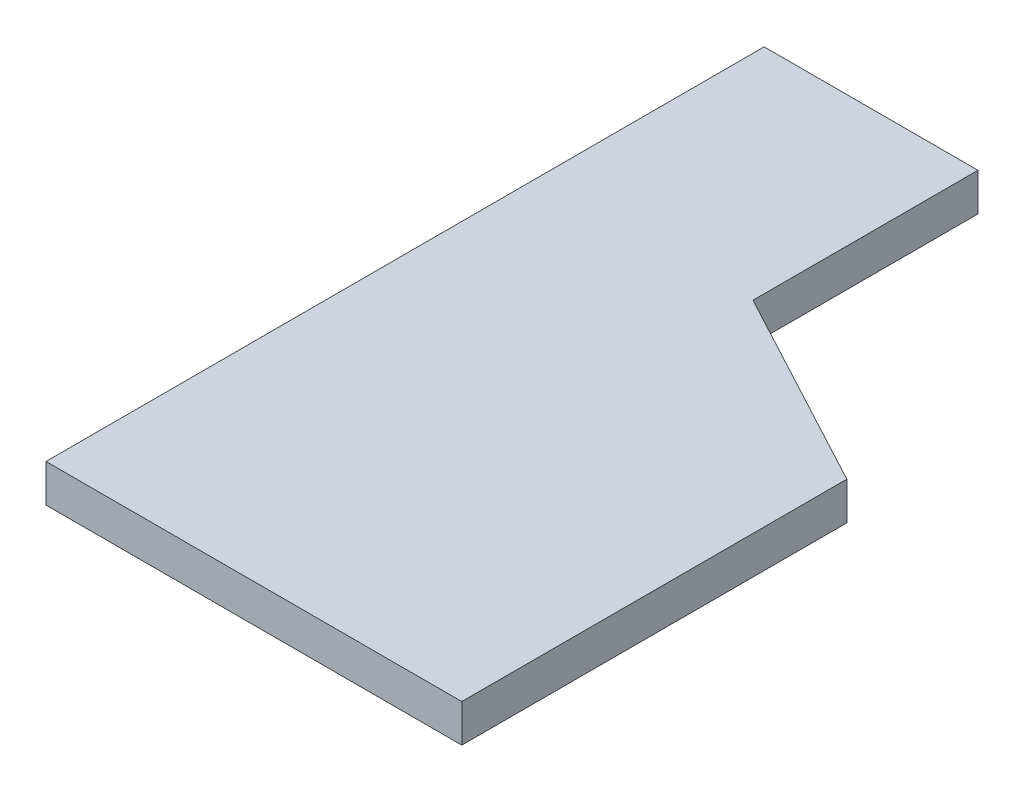
SolidWorks part; units mm, degrees
ref_plane "Front Plane" through (0, 0, 0) normal (0, 0, 1) x (1, 0, 0)
ref_plane "Top Plane" through (0, 0, 0) normal (0, 1, 0) x (1, 0, 0)
ref_plane "Right Plane" through (0, 0, 0) normal (1, 0, 0) x (0, 0, -1)
sketch "Sketch1" plane through (0, 0, 0) normal (0, 0, 1) x (1, 0, 0)
  line L1 (0, 0) -> (69.85, 0)
  line L2 (0, 0) -> (0, 6.35)
  line L3 (0, 6.35) -> (69.85, 6.35)
  line L4 (69.85, 0) -> (69.85, 6.35)
  dimension "D1" = 6.35
  dimension "D2" = 69.85
extrude "Boss-Extrude1" add sketch "Sketch1" along normal blind 120.65
sketch "Sketch2" plane through (0, 6.35, 0) normal (0, 1, 0) x (1, 0, 0)
  line L0 (35.9237, 0) -> (35.9237, -37.803)
  line L1 (69.85, 0) -> (35.9237, 0)
  line L2 (69.85, 0) -> (69.85, -55.9623)
  line L4 (35.9237, -37.803) -> (69.85, -55.9623)
extrude "Cut-Extrude1" cut sketch "Sketch2" against normal through all
